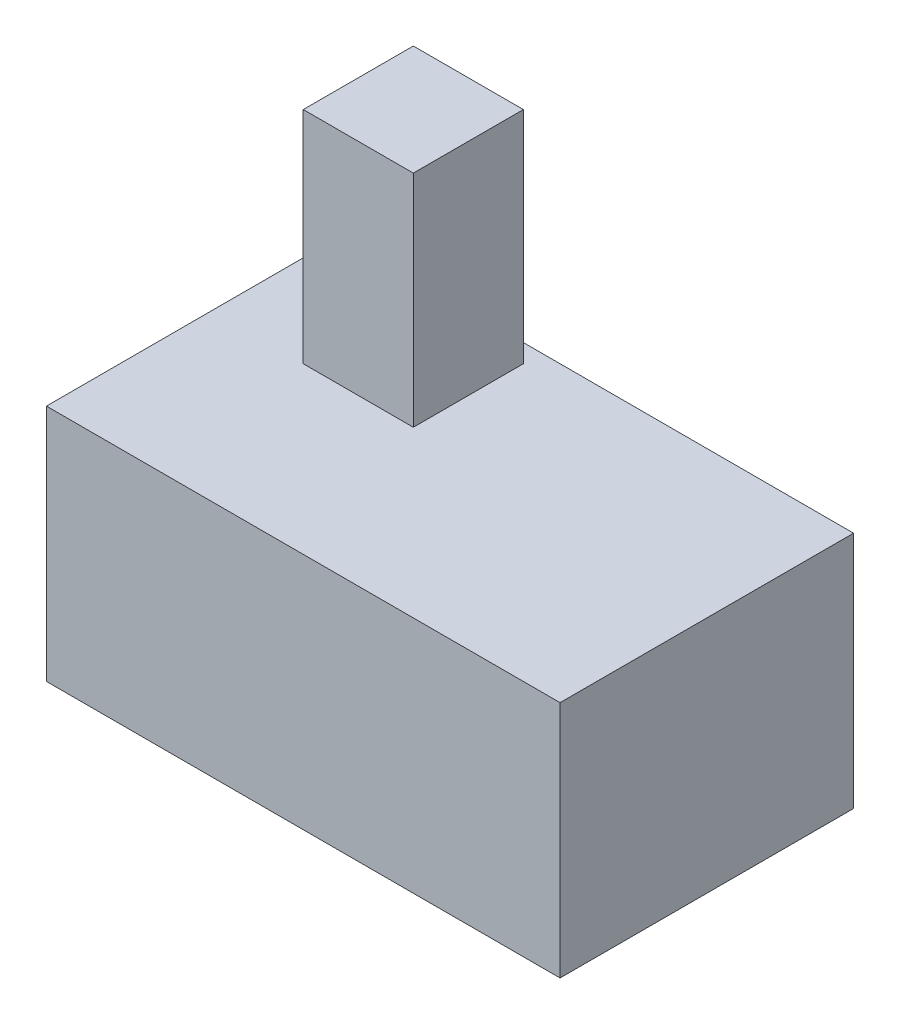
SolidWorks part; units mm, degrees
ref_plane "Front Plane" through (0, 0, 0) normal (0, 0, 1) x (1, 0, 0)
ref_plane "Top Plane" through (0, 0, 0) normal (0, 1, 0) x (1, 0, 0)
ref_plane "Right Plane" through (0, 0, 0) normal (1, 0, 0) x (0, 0, -1)
sketch "Sketch1" plane through (0, 0, 0) normal (0, 1, 0) x (1, 0, 0)
  line L1 (-7, -4) -> (7, -4)
  line L2 (-7, -4) -> (-7, 4)
  line L3 (-7, 4) -> (7, 4)
  line L4 (7, -4) -> (7, 4)
  line L5 (-7, -4) -> (7, 4) construction
  line L6 (-7, 4) -> (7, -4) construction
  point P0 (0, 0)
  dimension "D1" = 14
  dimension "D2" = 8
extrude "Boss-Extrude1" add sketch "Sketch1" along normal blind 6.5
sketch "Sketch2" plane through (0, 6.5, 0) normal (0, 1, 0) x (1, 0, 0)
  line L0 (7, 4) -> (-7, 4) construction
  line L1 (-4.5, 0.5) -> (-1.5, 0.5)
  line L2 (-4.5, 0.5) -> (-4.5, 3.5)
  line L3 (-4.5, 3.5) -> (-1.5, 3.5)
  line L4 (-1.5, 0.5) -> (-1.5, 3.5)
  line L5 (-4.5, 0.5) -> (-1.5, 3.5) construction
  line L6 (-4.5, 3.5) -> (-1.5, 0.5) construction
  point P0 (-3, 2)
  dimension "D1" = 3
  dimension "D2" = 3
  dimension "D3" = 3
  dimension "D4" = 2
extrude "Boss-Extrude2" add sketch "Sketch2" along normal blind 6
